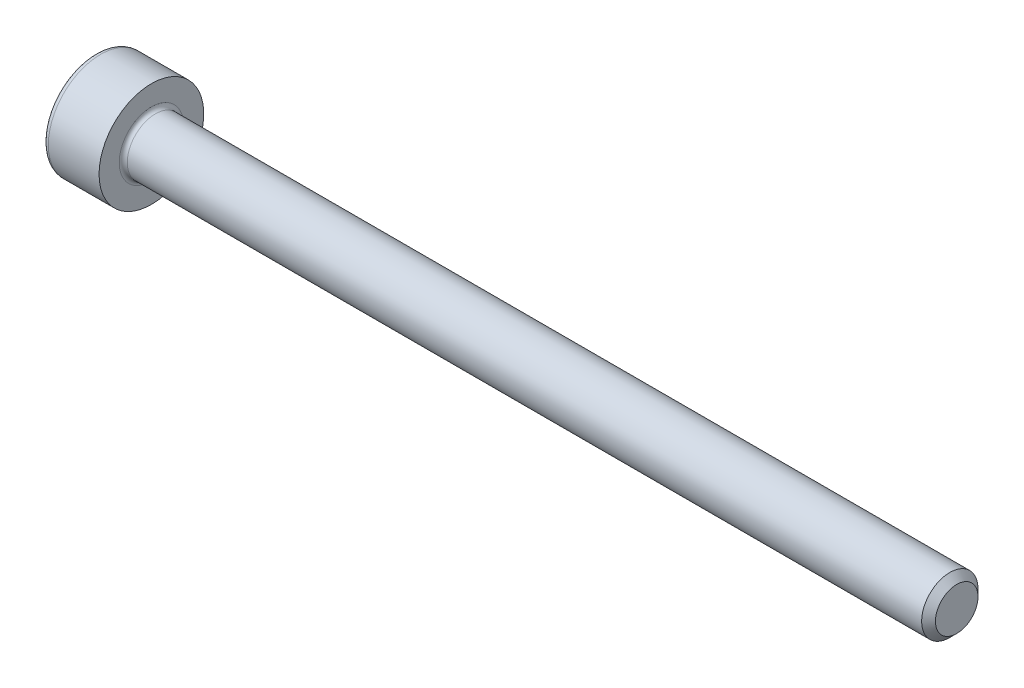
SolidWorks part; units mm, degrees
revolve "Base-Revolve" add sketch "BodySke"
sketch "BodySke" plane through (0, 0, 0) normal (0, 0, 1) x (1, 0, 0)
  line L0 (0, 0) -> (0, 1.3)
  line L1 (0, 1.3) -> (1.4, 1.3)
  line L2 (1.4, 1.3) -> (1.4, 0.7)
  line L3 (1.4, 0.7) -> (21.2285, 0.7)
  line L4 (21.4, 0.5285) -> (21.4, 0)
  line L5 (21.4, 0) -> (0, 0)
  line L6 (-31.75, 0) -> (127, 0) construction
  line L8 (21.4, 0.5285) -> (21.2285, 0.7)
  line L10 (21.4, -0.5285) -> (21.2285, -0.7) construction
  line L11 (1.7, 9.525) -> (1.7, 3.175) construction
  line L12 (11.4, 9.525) -> (11.4, 3.175) construction
  line L13 (-38.6, 9.525) -> (-38.6, 3.175) construction
  dimension "Head_ht" = 1.4
  dimension "Length" = 20
  dimension "Body_ch_ang" = 45
  dimension "Diameter" = 1.4
  dimension "Minor_dia" = 1.057
  dimension "Advance" = 0.3
  dimension "Thread_nom" = 10
  dimension "Thread_length" = 60
  dimension "Head_dia" = 2.6
cosmetic thread "ThreadCosmetic" [suppressed]
fillet "Fillet1" radius 0.1 1 edges at (1.4, 0, 0.7)
fillet "Fillet2" radius 0.14 1 edges at (0, 0, 1.3)
ref_plane "Plane1" through (0, 0, 0) normal (0, 0, 1) x (1, 0, 0)
ref_plane "Plane2" through (0, 0, 0) normal (0, 1, 0) x (1, 0, 0)
ref_plane "Plane3" through (0, 0, 0) normal (1, 0, 0) x (0, 0, -1)
sketch "Sketch2" plane through (0, 0, 0) normal (0, 0, 1) x (1, 0, 0)
  line L0 (0, 0.66) -> (0.6, 0.66)
  line L1 (0.6, 0.66) -> (0.9811, 0)
  line L2 (-31.75, 0) -> (127, 0) construction
  line L3 (0.9811, 0) -> (0, 0)
  line L4 (0, 0) -> (0, 0.66)
  line L6 (0, 0) -> (47.625, 0) construction
  dimension "D1" = 0.66
  dimension "D2" = 60
  dimension "Depth" = 0.6
revolve "Hex-PreBroach" cut sketch "Sketch2" angle 360 about L6
sketch "Sketch3" plane through (0, 0, 0) normal (-1, 0, 0) x (0, 0.5, 0.866)
  line L0 (0.3811, 0.66) -> (-0.3811, 0.66)
  line L1 (-0.3811, 0.66) -> (-0.7621, 0)
  line L2 (0.3811, 0.66) -> (0.7621, 0)
  line L3 (0.3811, -0.66) -> (0.7621, 0)
  line L4 (0.3811, -0.66) -> (-0.3811, -0.66)
  line L5 (-0.3811, -0.66) -> (-0.7621, 0)
  dimension "D1" = 0.66
  dimension "D2" = 0.66
  dimension "Hex_size" = 1.32
extrude "Hex" cut sketch "Sketch3" against normal blind 0.6
sketch "ThdSchSke" plane through (0, 0, 0) normal (0, 0, 1) x (1, 0, 0)
  line L0 (11.4, -0.5285) -> (11.2799, -0.7)
  line L1 (11.4, -0.5285) -> (11.5201, -0.7)
  line L2 (11.5201, -0.7) -> (11.5201, -0.875)
  line L3 (-3.175, 0) -> (5.1513, 0) construction
  line L4 (0, 1.16) -> (0, -1.16) construction
  line L5 (11.5201, -0.875) -> (11.2799, -0.875)
  line L6 (11.2799, -0.875) -> (11.2799, -0.7)
  dimension "Thread_minor" = 1.057
  dimension "Diameter" = 1.4
  dimension "Start" = 11.4
revolve "ThreadSchematic" [suppressed] cut sketch "ThdSchSke" angle 360 about L3
pattern_linear "ThdSchPat" [suppressed]
equation "\"D2@Sketch3\" = \"Hex_size@Sketch3\" / 2"
equation "\"D1@Sketch3\" = \"Hex_size@Sketch3\" / 2"
equation "\"D1@Sketch2\" = \"Hex_size@Sketch3\" / 2"
equation "\"Thread_minor@ThreadCosmetic\"  =  \"Minor_dia@BodySke\""
equation "\"Depth@Sketch2\" =  \"Key_eng@Hex\""
equation "\"Thread_length@ThreadCosmetic\" = ((sgn( (\"Length@BodySke\" - \"Advance@BodySke\" * 3.0) - \"Thread_nom@BodySke\" )-1)*( (\"Length@BodySke\" - \"Advance@BodySke\" * 3.0) - \"Thread_nom@BodySke\" ))/-2+ \"Thread_nom@BodySke\""
equation "\"Thread_minor@ThdSchSke\" = \"Minor_dia@BodySke\""
equation "\"Diameter@ThdSchSke\" = \"Diameter@BodySke\""
equation "\"Overcut@ThdSchSke\" = \"Diameter@BodySke\" * 1.25"
equation "\"Start@ThdSchSke\" = \"Head_ht@BodySke\" + \"Length@BodySke\" - \"Thread_length@ThreadCosmetic\"  '---Non-countersunk---"
equation "\"Num_threads@ThdSchPat\" = int( \"Thread_length@ThreadCosmetic\" / \"Advance@BodySke\" + 0.999 )  + 1"
equation "\"Advance@ThdSchPat\" = \"Thread_length@ThreadCosmetic\" /  (\"Num_threads@ThdSchPat\" - 1) 'relax it"
equation "\"Num_threads@ThdSchPat\" = \"Num_threads@ThdSchPat\" - sgn( \"Num_threads@ThdSchPat\" - 1) '---chamfered tips only---"
